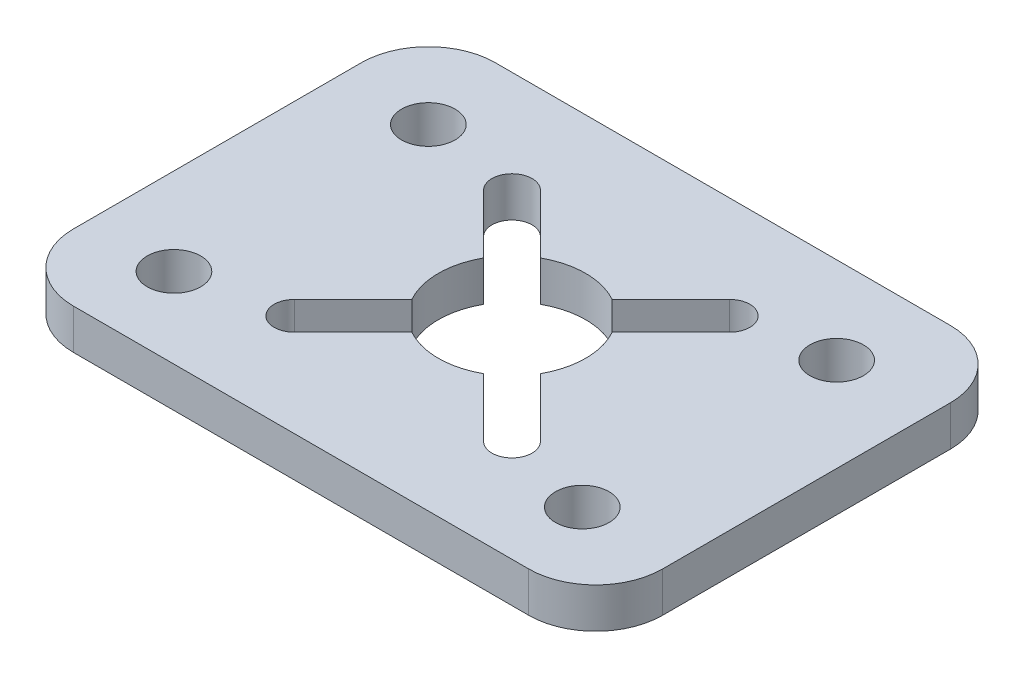
SolidWorks part; units mm, degrees
ref_plane "Front Plane" through (0, 0, 0) normal (0, 0, 1) x (1, 0, 0)
ref_plane "Top Plane" through (0, 0, 0) normal (0, 1, 0) x (1, 0, 0)
ref_plane "Right Plane" through (0, 0, 0) normal (1, 0, 0) x (0, 0, -1)
sketch "Sketch1" plane through (0, 0, 0) normal (0, 1, 0) x (1, 0, 0)
  line L1 (0, 0) -> (44, 0)
  line L2 (0, 0) -> (0, 31.5)
  line L3 (0, 31.5) -> (44, 31.5)
  line L4 (44, 0) -> (44, 31.5)
  dimension "D1" = 44
  dimension "D2" = 31.5
extrude "Boss-Extrude1" add sketch "Sketch1" along normal blind 3
sketch "Sketch2" plane through (0, 3, 0) normal (0, 1, 0) x (1, 0, 0)
  line L0 (0, 0) -> (44, 0) construction
  line L1 (44, 0) -> (44, 31.5) construction
  circle A0 centre (22, 15.75) radius 5.5
  point P2 (22, 0)
  point P5 (44, 15.75)
  dimension "D1" = 11
  dimension "D2" = 0
  dimension "D3" = 0
extrude "Cut-Extrude1" cut sketch "Sketch2" against normal blind 3
sketch "Sketch3" plane through (0, 3, 0) normal (0, 1, 0) x (1, 0, 0)
  line L0 (13.8683, 23.8817) -> (30.1317, 7.6183) construction
  line L1 (14.9289, 24.9424) -> (31.1924, 8.6789)
  line L2 (12.8076, 22.8211) -> (29.0711, 6.5576)
  line L3 (0, 0) -> (44, 0) construction
  arc A0 (14.9289, 24.9424) -> (12.8076, 22.8211) centre (13.8683, 23.8817) ccw
  arc A1 (29.0711, 6.5576) -> (31.1924, 8.6789) centre (30.1317, 7.6183) ccw
  point P2 (22, 15.75)
  dimension "D3" = 1.5
  dimension "D1" = 23
  dimension "D2" = 45
extrude "Cut-Extrude2" cut sketch "Sketch3" against normal blind 3
sketch "Sketch4" plane through (0, 3, 0) normal (0, 1, 0) x (1, 0, 0)
  line L0 (30.1317, 23.8817) -> (13.8683, 7.6183) construction
  line L1 (31.1924, 22.8211) -> (14.9289, 6.5576)
  line L2 (29.0711, 24.9424) -> (12.8076, 8.6789)
  line L3 (0, 0) -> (44, 0) construction
  arc A0 (31.1924, 22.8211) -> (29.0711, 24.9424) centre (30.1317, 23.8817) ccw
  arc A1 (12.8076, 8.6789) -> (14.9289, 6.5576) centre (13.8683, 7.6183) ccw
  point P2 (22, 15.75)
  dimension "D2" = 1.5
  dimension "D1" = 23
  dimension "D3" = 45
extrude "Cut-Extrude3" cut sketch "Sketch4" against normal blind 3
sketch "Sketch5" plane through (0, 3, 0) normal (0, 1, 0) x (1, 0, 0)
  line L0 (44, 31.5) -> (0, 31.5) construction
  line L1 (0, 31.5) -> (0, 0) construction
  circle A0 centre (6.5, 25) radius 2
  dimension "D1" = 4
  dimension "D2" = 6.5
  dimension "D3" = 6.5
extrude "Cut-Extrude4" cut sketch "Sketch5" against normal blind 3
pattern_linear "LPattern1" count 2 spacing 30.5 along (1, 0, 0) count 2 spacing 19 along (0, 0, 1) of "Cut-Extrude4"
fillet "Fillet1" radius 5 4 edges at (44, 1.5, -31.5) (44, 1.5, 0) (0, 1.5, 0) (0, 1.5, -31.5)
